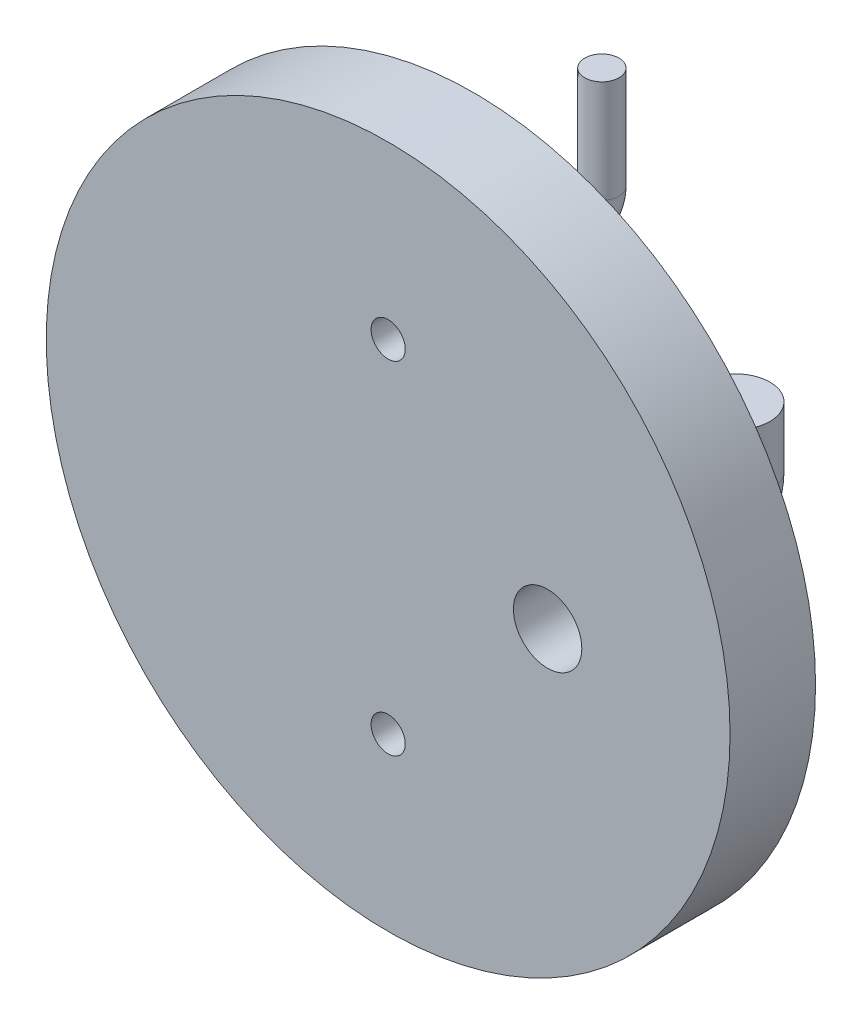
SolidWorks part; units mm, degrees
ref_plane "Front Plane" through (0, 0, 0) normal (0, 0, 1) x (1, 0, 0)
ref_plane "Top Plane" through (0, 0, 0) normal (0, 1, 0) x (1, 0, 0)
ref_plane "Right Plane" through (0, 0, 0) normal (1, 0, 0) x (0, 0, -1)
sketch "Sketch1" plane through (0, 0, 0) normal (0, 0, 1) x (1, 0, 0)
  line L0 (0, -55) -> (0, 55) construction
  circle A0 centre (0, 0) radius 40
  circle A1 centre (0, 20) radius 2
  circle A2 centre (0, -20) radius 2
  circle A3 centre (18.6528, 0) radius 4
  point P11 (18.6528, 4.9955)
  dimension "D1" = 80
  dimension "D2" = 20
  dimension "D3" = 20
extrude "Boss-Extrude1" add sketch "Sketch1" along normal blind 10
sketch "Sketch2" plane through (0, 0, 0) normal (1, 0, 0) x (0, 0, -1)
  line L2 (17, 23) -> (17, 35)
  line L6 (0, 55) -> (0, -55) construction
  line L7 (0, 18) -> (12, 18)
  arc A0 (17, 23) -> (12, 18) centre (12, 23) cw
  dimension "D1" = 5
sketch "Sketch3" plane through (0, 0, 0) normal (0, 0, -1) x (-1, 0, 0)
  circle A0 centre (0, 20) radius 2
sketch "Sketch4" plane through (0, 0, 0) normal (1, 0, 0) x (0, 0, -1)
  line L0 (17, -23) -> (17, -35)
  line L4 (0, 55) -> (0, -55) construction
  line L5 (12, -18) -> (0, -18)
  arc A0 (17, -23) -> (12, -18) centre (12, -23) ccw
  dimension "D1" = 5
sketch "Sketch5" plane through (0, 0, 0) normal (0, 0, 1) x (1, 0, 0)
  circle A0 centre (0, -20) radius 2
sweep "Sweep4" add profiles "Sketch5" path "Sketch4"
sweep "Sweep5" add profiles "Sketch3" path "Sketch2"
sketch "Sketch6" plane through (0, 0, 0) normal (0, 0, 1) x (1, 0, 0)
  circle A0 centre (18.6528, 0) radius 4
ref_plane "Plane1" through (18.6528, 0, 0) normal (1, 0, 0) x (0, 0, -1)
sketch "Sketch8" plane through (18.6528, 0, 0) normal (1, 0, 0) x (0, 0, -1)
  line L0 (0, 0) -> (7, 0)
  line L1 (14.85, 0) -> (-14.85, 0) construction
  line L2 (12, 5) -> (12, 12)
  arc A0 (12, 5) -> (7, 0) centre (7, 5) cw
  point P8 (12, 0)
  dimension "D1" = 5
sweep "Sweep6" add profiles "Sketch6" path "Sketch8"
